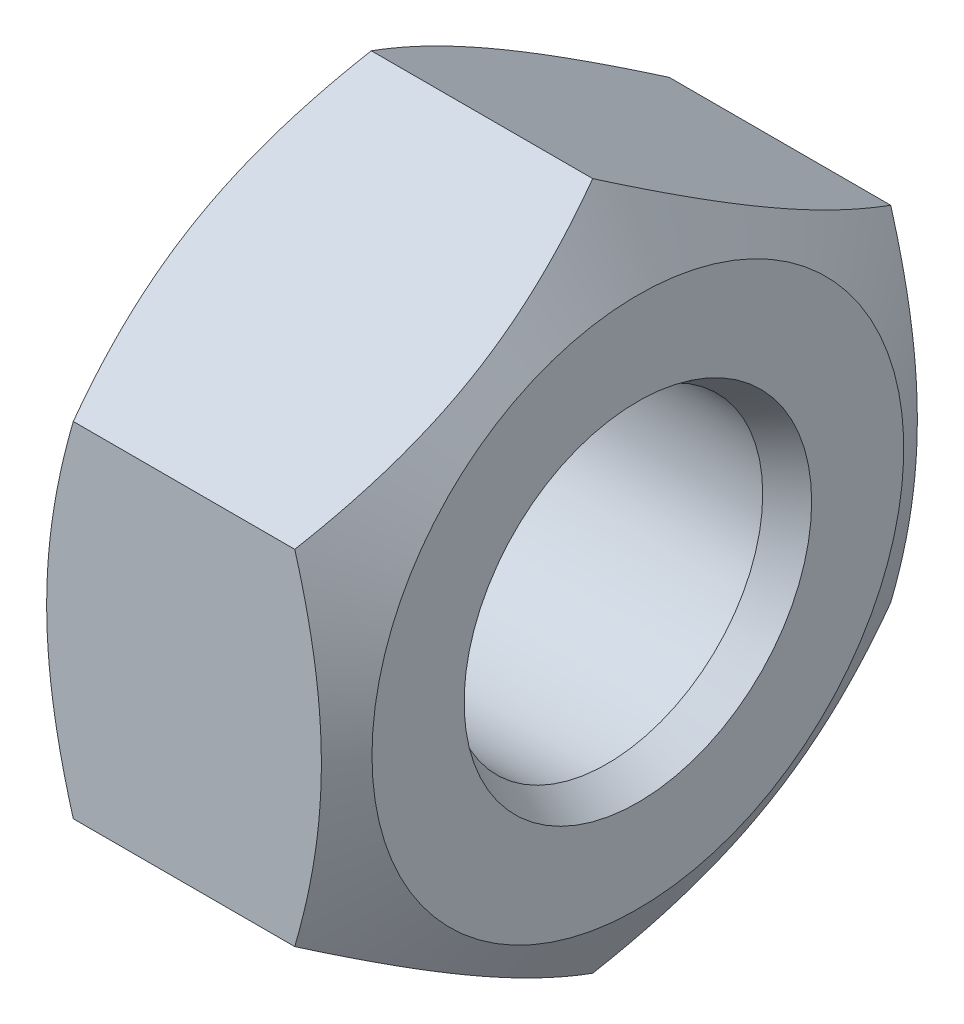
SolidWorks part; units mm, degrees
material "Steel"
ref_plane "Front Plane" through (0, 0, 0) normal (0, 0, 1) x (1, 0, 0)
ref_plane "Top Plane" through (0, 0, 0) normal (0, 1, 0) x (1, 0, 0)
ref_plane "Right Plane" through (0, 0, 0) normal (1, 0, 0) x (0, 0, -1)
ref_plane "Plane1"
sketch "Sketch1" plane through (0, 0, 0) normal (1, 0, 0) x (0, 1, 0)
  line L0 (-7.5056, 0) -> (-3.7528, 6.5)
  line L1 (-3.7528, 6.5) -> (3.7528, 6.5)
  line L2 (3.7528, 6.5) -> (7.5056, 0)
  line L3 (7.5056, 0) -> (3.7528, -6.5)
  line L4 (3.7528, -6.5) -> (-3.7528, -6.5)
  line L5 (-3.7528, -6.5) -> (-7.5056, 0)
  dimension "D1" = 15.0111
extrude "Body" add sketch "Sketch1" along normal blind 6.8
ref_plane "Plane2"
sketch "Sketch2" plane through (0, 0, 0) normal (0, 0, 1) x (1, 0, 0)
  line L0 (0, 7.5056) -> (0, 5.8)
  line L1 (0, 5.8) -> (0.9847, 7.5056)
  line L2 (0.9847, 7.5056) -> (0, 7.5056)
  line L3 (-1.36, 0) -> (8.16, 0) construction
  line L4 (5.8153, 7.5056) -> (6.8, 5.8)
  line L5 (6.8, 5.8) -> (6.8, 7.5056)
  line L6 (6.8, 7.5056) -> (5.8153, 7.5056)
  line L7 (0, 7.5056) -> (0, 3.7528) construction
  line L8 (6.8, 7.5056) -> (6.8, 3.7528) construction
  dimension "D1" = 150
  dimension "D2" = 150
  dimension "D3" = 90
  dimension "D4" = 120
revolve "Chamfer1" cut sketch "Sketch2" angle 360 about L3
hole_wizard "Thread" positions "Sketch4" profile "Sketch3" tap size "M8x1.25" standard "Ansi Metric" end condition through all
sketch "Sketch4" plane through (6.8, 0, 0) normal (1, 0, 0) x (0, 0, -1)
  point P1 (0, 0)
sketch "Sketch3" plane through (6.8, 0, 0) normal (0, 1, 0) x (0, 0, -1)
  line L0 (0, 0) -> (0, 6.8)
  line L1 (0, 6.8) -> (3.4, 6.8)
  line L2 (3.4, 6.8) -> (3.4, 0)
  line L5 (3.4, 0) -> (0, 0)
  line L11 (0, -6.35) -> (0, 107.95) construction
  dimension "Thru Tap Drill Dia." = 6.8
  dimension "Thru Tap Drill Depth" = 6.8
cosmetic thread "Hole Thread1" parameters "D2"=8
chamfer "Chamfer3" distance 0.6766 angle 30 2 edges at (0, 0, -3.4) (6.8, 0, -3.4)
